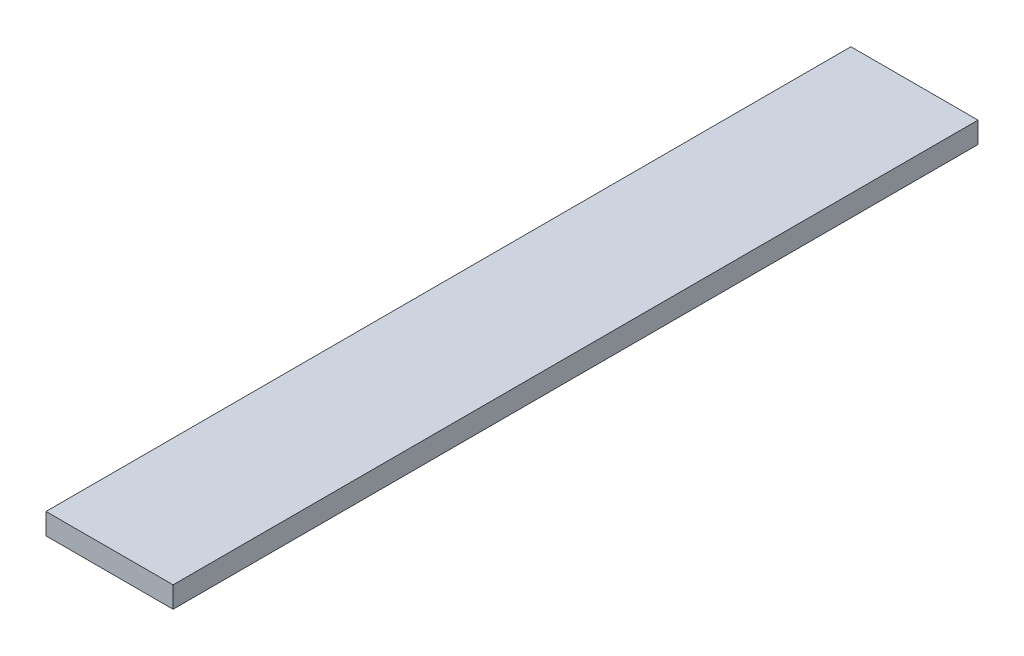
SolidWorks part; units mm, degrees
ref_plane "Front" through (0, 0, 0) normal (0, 0, 1) x (1, 0, 0)
ref_plane "Top" through (0, 0, 0) normal (0, 1, 0) x (1, 0, 0)
ref_plane "Right" through (0, 0, 0) normal (1, 0, 0) x (0, 0, -1)
sketch "Sketch1" plane through (0, 0, 0) normal (0, 0, 1) x (1, 0, 0)
  line L1 (-19.05, 3.175) -> (19.05, 3.175)
  line L2 (-19.05, 3.175) -> (-19.05, -3.175)
  line L3 (-19.05, -3.175) -> (19.05, -3.175)
  line L4 (19.05, 3.175) -> (19.05, -3.175)
  line L5 (-19.05, 3.175) -> (19.05, -3.175) construction
  line L6 (-19.05, -3.175) -> (19.05, 3.175) construction
  point P0 (0, 0)
  dimension "D1" = 6.35
  dimension "D2" = 38.1
extrude "Boss-Extrude1" add sketch "Sketch1" along normal blind 241.3
